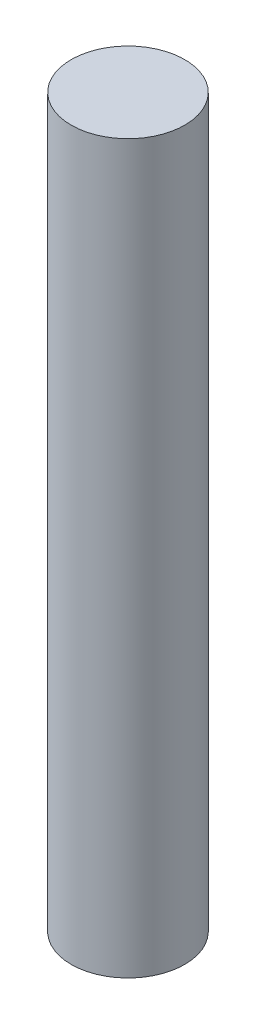
SolidWorks part; units mm, degrees
material "1023 Carbon Steel Sheet (SS)"
ref_plane "Front Plane" through (0, 0, 0) normal (0, 0, 1) x (1, 0, 0)
ref_plane "Top Plane" through (0, 0, 0) normal (0, 1, 0) x (1, 0, 0)
ref_plane "Right Plane" through (0, 0, 0) normal (1, 0, 0) x (0, 0, -1)
sketch "Sketch1" plane through (0, 0, 0) normal (0, 1, 0) x (1, 0, 0)
  circle A0 centre (-25.6161, 7.19) radius 2.5
  dimension "D1" = 5
extrude "Boss-Extrude1" add sketch "Sketch1" along normal blind 32
